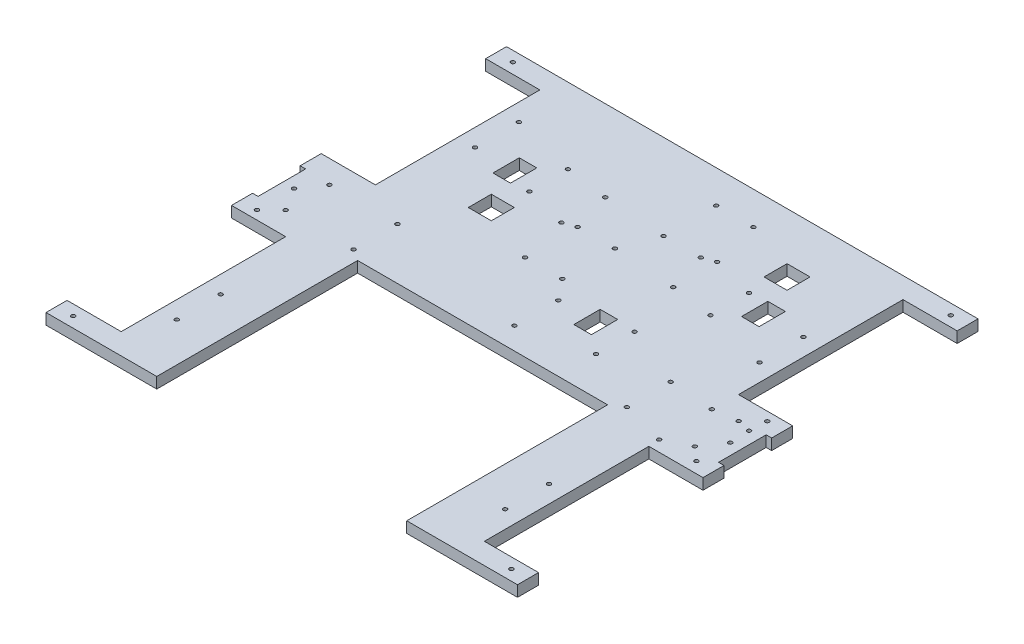
SolidWorks part; units mm, degrees
material "Acrylic (Medium-high impact)"
ref_plane "Front Plane" through (0, 0, 0) normal (0, 0, 1) x (1, 0, 0)
ref_plane "Top Plane" through (0, 0, 0) normal (0, 1, 0) x (1, 0, 0)
ref_plane "Right Plane" through (0, 0, 0) normal (1, 0, 0) x (0, 0, -1)
sketch "Sketch1" plane through (0, 0, 0) normal (0, 1, 0) x (1, 0, 0)
  line L0 (0, 0) -> (60.96, 0)
  line L2 (0, 0) -> (0, 266.7)
  line L3 (0, 266.7) -> (266.7, 266.7)
  line L4 (266.7, 0) -> (266.7, 266.7)
  line L5 (266.7, 0) -> (205.74, 0)
  line L6 (60.96, 0) -> (60.96, 116.332)
  line L7 (60.96, 116.332) -> (205.74, 116.332)
  line L8 (205.74, 116.332) -> (205.74, 0)
  line L9 (131.445, 116.332) -> (144.399, 116.332) construction
  dimension "D1" = 266.7
  dimension "D2" = 60.96
extrude "Boss-Extrude1" add sketch "Sketch1" along normal blind 6.35
sketch "Sketch3" plane through (0, 0, 0) normal (0, -1, 0) x (1, 0, 0)
  line L1 (6.5151, -160.02) -> (260.1849, -160.02) construction
  line L2 (6.5151, -160.02) -> (6.5151, -254) construction
  line L3 (6.5151, -254) -> (260.1849, -254) construction
  line L4 (260.1849, -160.02) -> (260.1849, -254) construction
  line L5 (200.2409, -199.39) -> (210.4009, -199.39)
  line L6 (56.2737, -199.39) -> (66.4337, -199.39)
  line L7 (56.2737, -199.39) -> (56.2737, -214.63)
  line L8 (56.2737, -214.63) -> (66.4337, -214.63)
  line L9 (66.4337, -199.39) -> (66.4337, -214.63)
  line L10 (200.2409, -199.39) -> (200.2409, -214.63)
  line L11 (200.2409, -214.63) -> (210.4009, -214.63)
  line L12 (210.4009, -199.39) -> (210.4009, -214.63)
  line L13 (266.7, -266.7) -> (0, -266.7) construction
  circle A0 centre (38.2651, -232.41) radius 1.1303
  circle A1 centre (38.2651, -207.01) radius 1.1303
  circle A2 centre (76.0857, -223.012) radius 1.1303
  circle A3 centre (76.0857, -200.66) radius 1.1303
  circle A4 centre (107.8611, -166.37) radius 1.1303
  circle A5 centre (107.8611, -196.85) radius 1.1303
  circle A6 centre (129.4511, -166.37) radius 1.1303
  circle A7 centre (129.4511, -196.85) radius 1.1303
  circle A8 centre (137.2743, -217.17) radius 1.1303
  circle A9 centre (158.8643, -217.17) radius 1.1303
  circle A10 centre (137.2743, -247.65) radius 1.1303
  circle A11 centre (158.8643, -247.65) radius 1.1303
  circle A12 centre (190.5889, -191.008) radius 1.1303
  circle A13 centre (190.5889, -213.36) radius 1.1303
  circle A14 centre (228.4349, -181.61) radius 1.1303
  circle A15 centre (228.4349, -207.01) radius 1.1303
  point P6 (133.35, -266.7)
  point P7 (133.35, -160.02)
  point P52 (133.35, -254)
  dimension "D4" = 10.16
  dimension "D30" = 31.75
  dimension "D12" = 2.2606
  dimension "D1" = 93.98
  dimension "D2" = 253.6698
  dimension "D3" = 12.7
  dimension "D5" = 15.24
  dimension "D6" = 25.4
  dimension "D7" = 31.75
  dimension "D8" = 30.48
  dimension "D9" = 21.59
  dimension "D10" = 130.7592
  dimension "D11" = 6.35
  dimension "D13" = 39.37
  dimension "D14" = 21.59
  dimension "D15" = 49.7586
  dimension "D16" = 22.352
  dimension "D17" = 69.5706
  dimension "D18" = 30.988
  dimension "D19" = 21.59
  dimension "D20" = 30.48
  dimension "D21" = 152.3238
  dimension "D22" = 6.35
  dimension "D23" = 22.352
  dimension "D24" = 30.988
  dimension "D25" = 69.596
  dimension "D26" = 49.784
  dimension "D27" = 39.37
  dimension "D28" = 25.4
  dimension "D29" = 21.59
extrude "Cut-Extrude1" cut sketch "Sketch3" against normal blind 6.35
sketch "Sketch5" plane through (0, 0, 0) normal (0, 1, 0) x (1, 0, 0)
  line L0 (0, 266.7) -> (0, 0) construction
  line L1 (0, 254.635) -> (28.194, 254.635)
  line L2 (0, 254.635) -> (0, 159.385)
  line L3 (0, 159.385) -> (28.194, 159.385)
  line L4 (28.194, 254.635) -> (28.194, 159.385)
  line L5 (266.7, 0) -> (266.7, 266.7) construction
  line L6 (266.7, 254.635) -> (238.506, 254.635)
  line L7 (266.7, 254.635) -> (266.7, 159.385)
  line L8 (266.7, 159.385) -> (238.506, 159.385)
  line L9 (238.506, 254.635) -> (238.506, 159.385)
  line L10 (266.7, 107.442) -> (238.506, 107.442)
  line L11 (266.7, 107.442) -> (266.7, 12.192)
  line L12 (266.7, 12.192) -> (238.506, 12.192)
  line L13 (238.506, 107.442) -> (238.506, 12.192)
  line L14 (266.7, 266.7) -> (0, 266.7) construction
  line L15 (205.74, 0) -> (266.7, 0) construction
  line L16 (266.7, 0) -> (266.7, 266.7) construction
  line L17 (28.194, 107.442) -> (0, 107.442)
  line L18 (28.194, 107.442) -> (28.194, 12.192)
  line L19 (28.194, 12.192) -> (0, 12.192)
  line L20 (0, 107.442) -> (0, 12.192)
  line L21 (0, 0) -> (60.96, 0) construction
  point P6 (28.194, 207.01)
  point P17 (238.506, 207.01)
  dimension "D1" = 95.25
  dimension "D2" = 28.194
  dimension "D3" = 95.25
  dimension "D4" = 28.194
  dimension "D5" = 12.065
  dimension "D6" = 12.192
  dimension "D7" = 12.192
extrude "Cut-Extrude2" cut sketch "Sketch5" along normal blind 6.35
sketch "Sketch6" plane through (0, 6.35, 0) normal (0, 1, 0) x (1, 0, 0)
  line L0 (129.4511, 196.85) -> (129.4511, 166.37) construction
  line L1 (66.4337, 188.2789) -> (79.7715, 188.2789)
  line L2 (66.4337, 188.2789) -> (66.4337, 174.9411)
  line L3 (66.4337, 174.9411) -> (79.7715, 174.9411)
  line L4 (79.7715, 188.2789) -> (79.7715, 174.9411)
  line L5 (137.2743, 247.65) -> (137.2743, 217.17) construction
  line L7 (186.9031, 239.0789) -> (200.2409, 239.0789)
  line L8 (186.9031, 239.0789) -> (186.9031, 225.7411)
  line L9 (186.9031, 225.7411) -> (200.2409, 225.7411)
  line L10 (200.2409, 239.0789) -> (200.2409, 225.7411)
  line L12 (66.4337, 214.63) -> (66.4337, 199.39) construction
  line L13 (200.2409, 199.39) -> (200.2409, 214.63) construction
  point P8 (129.4511, 181.61)
  point P9 (66.4337, 181.61)
  point P19 (200.2409, 232.41)
  point P20 (137.2743, 232.41)
extrude "Cut-Extrude3" cut sketch "Sketch6" against normal blind 6.35
sketch "Sketch7" plane through (0, 0, 0) normal (0, -1, 0) x (1, 0, 0)
  line L0 (0, -159.385) -> (0, -107.442) construction
  line L1 (28.194, -107.442) -> (0, -107.442) construction
  line L2 (0, -159.385) -> (28.194, -159.385) construction
  line L3 (266.7, -107.442) -> (266.7, -159.385) construction
  line L4 (266.7, -107.442) -> (238.506, -107.442) construction
  line L5 (238.506, -159.385) -> (266.7, -159.385) construction
  line L7 (0, 0) -> (60.96, 0) construction
  circle A0 centre (3.81, -113.792) radius 1.1303 construction
  circle A1 centre (3.81, -153.035) radius 1.1303 construction
  circle A2 centre (262.89, -113.792) radius 1.1303 construction
  circle A5 centre (262.89, -153.035) radius 1.1303 construction
  circle A6 centre (44.45, -113.792) radius 1.1303 construction
  circle A7 centre (44.45, -153.035) radius 1.1303 construction
  circle A8 centre (222.25, -113.792) radius 1.1303 construction
  circle A9 centre (222.25, -153.035) radius 1.1303 construction
  circle A10 centre (38.2651, -34.29) radius 1.1303
  circle A11 centre (38.2651, -59.69) radius 1.1303
  circle A12 centre (228.4349, -34.29) radius 1.1303
  circle A13 centre (228.4349, -59.69) radius 1.1303
  dimension "D1" = 2.2606
  dimension "D2" = 3.81
  dimension "D3" = 6.35
  dimension "D4" = 6.35
  dimension "D5" = 3.81
  dimension "D6" = 3.81
  dimension "D7" = 6.35
  dimension "D8" = 6.35
  dimension "D9" = 40.64
  dimension "D10" = 40.64
  dimension "D11" = 39.243
  dimension "D12" = 25.4
  dimension "D14" = 34.29
extrude "Cut-Extrude4" cut sketch "Sketch7" against normal blind 16.002
sketch "Sketch8" plane through (0, 6.35, 0) normal (0, 1, 0) x (1, 0, 0)
  line L0 (266.7, 107.442) -> (266.7, 159.385) construction
  line L2 (14.859, 146.1135) -> (14.859, 120.7135) construction
  line L3 (0, 159.385) -> (0, 107.442) construction
  line L4 (14.859, 146.1135) -> (54.229, 146.1135) construction
  line L5 (28.194, 159.385) -> (28.194, 254.635) construction
  line L6 (212.471, 146.1135) -> (251.841, 146.1135) construction
  line L7 (155.702, 162.052) -> (165.862, 162.052)
  line L8 (238.506, 254.635) -> (238.506, 159.385) construction
  line L9 (155.702, 162.052) -> (155.702, 146.812)
  line L10 (155.702, 146.812) -> (165.862, 146.812)
  line L11 (165.862, 162.052) -> (165.862, 146.812)
  line L13 (238.506, 159.385) -> (266.7, 159.385) construction
  circle A0 centre (14.859, 146.1135) radius 1.1303
  circle A1 centre (14.859, 120.7135) radius 1.1303
  circle A2 centre (107.8611, 166.37) radius 1.1303 construction
  circle A3 centre (54.229, 146.1135) radius 1.1303
  circle A4 centre (54.229, 120.7135) radius 1.1303
  circle A5 centre (212.471, 146.1135) radius 1.1303
  circle A6 centre (212.471, 120.7135) radius 1.1303
  circle A8 centre (251.841, 120.7135) radius 1.1303
  circle A9 centre (251.841, 146.1135) radius 1.1303
  circle A10 centre (139.065, 154.432) radius 1.1303
  circle A11 centre (139.065, 129.032) radius 1.1303
  circle A14 centre (176.911, 160.782) radius 1.1303
  circle A16 centre (176.911, 138.43) radius 1.1303
  circle A17 centre (238.125, 144.272) radius 1.1303
  circle A18 centre (238.125, 113.792) radius 1.1303
  circle A19 centre (259.715, 144.272) radius 1.1303
  circle A20 centre (259.715, 113.792) radius 1.1303
  point P8 (232.156, 146.1135)
  point P10 (0, 133.4135)
  point P11 (14.859, 133.4135)
  point P17 (34.544, 146.1135)
  point P23 (160.782, 162.052)
  dimension "D1" = 25.4
  dimension "D2" = 39.37
  dimension "D3" = 6.35
  dimension "D4" = 39.37
  dimension "D5" = 6.35
  dimension "D6" = 6.985
  dimension "D7" = 15.113
  dimension "D8" = 30.48
  dimension "D9" = 21.59
  dimension "D10" = 21.59
  dimension "D11" = 61.214
  dimension "D12" = 22.352
  dimension "D13" = 5.842
  dimension "D14" = 10.16
  dimension "D15" = 15.24
  dimension "D16" = 16.129
  dimension "D17" = 1.27
  dimension "D18" = 25.4
  dimension "D19" = 37.846
  dimension "D20" = 7.62
extrude "Cut-Extrude5" cut sketch "Sketch8" against normal blind 6.35
sketch "Sketch9" plane through (0, 0, 0) normal (-1, 0, 0) x (0, 0, 1)
  line L0 (-159.385, 0) -> (-107.442, 0) construction
  line L1 (-266.7, 6.35) -> (-254.635, 6.35)
  line L2 (-266.7, 6.35) -> (-266.7, 0)
  line L3 (-266.7, 0) -> (-254.635, 0)
  line L4 (-254.635, 6.35) -> (-254.635, 0)
  line L5 (-12.192, 6.35) -> (0, 6.35)
  line L6 (-12.192, 6.35) -> (-12.192, 0)
  line L7 (-12.192, 0) -> (0, 0)
  line L8 (0, 6.35) -> (0, 0)
  line L9 (-159.385, 6.35) -> (-147.193, 6.35)
  line L10 (-159.385, 6.35) -> (-159.385, 0)
  line L11 (-159.385, 0) -> (-147.193, 0)
  line L12 (-147.193, 6.35) -> (-147.193, 0)
  line L13 (-159.385, 6.35) -> (-107.442, 6.35) construction
  line L14 (-107.442, 0) -> (-119.634, 0)
  line L15 (-107.442, 0) -> (-107.442, 6.35)
  line L16 (-107.442, 6.35) -> (-119.634, 6.35)
  line L17 (-119.634, 0) -> (-119.634, 6.35)
  dimension "D1" = 12.065
  dimension "D2" = 6.35
  dimension "D3" = 12.192
  dimension "D4" = 12.192
extrude "Boss-Extrude2" add sketch "Sketch9" along normal blind 3.175
sketch "Sketch10" plane through (266.7, 0, 0) normal (1, 0, 0) x (0, 0, -1)
  line L0 (107.442, 0) -> (159.385, 0) construction
  line L1 (0, 6.35) -> (12.192, 6.35)
  line L2 (0, 6.35) -> (0, 0)
  line L3 (0, 0) -> (12.192, 0)
  line L4 (12.192, 6.35) -> (12.192, 0)
  line L5 (107.442, 6.35) -> (119.634, 6.35)
  line L6 (107.442, 6.35) -> (107.442, 0)
  line L7 (107.442, 0) -> (119.634, 0)
  line L8 (119.634, 6.35) -> (119.634, 0)
  line L9 (159.385, 6.35) -> (147.193, 6.35)
  line L10 (159.385, 6.35) -> (159.385, 0)
  line L11 (159.385, 0) -> (147.193, 0)
  line L12 (147.193, 6.35) -> (147.193, 0)
  line L13 (254.635, 6.35) -> (266.7, 6.35) construction
  line L14 (254.635, 0) -> (266.7, 0)
  line L15 (254.635, 0) -> (254.635, 6.35)
  line L16 (254.635, 6.35) -> (266.7, 6.35)
  line L17 (266.7, 0) -> (266.7, 6.35)
  dimension "D1" = 12.192
  dimension "D2" = 12.192
extrude "Boss-Extrude3" add sketch "Sketch10" along normal blind 3.175
sketch "Sketch12" plane through (0, 6.35, 0) normal (0, 1, 0) x (1, 0, 0)
  circle A0 centre (100.965, 219.71) radius 1.1303
  circle A1 centre (107.8611, 166.37) radius 1.1303 construction
  circle A2 centre (100.965, 194.31) radius 1.1303
  circle A3 centre (165.735, 219.71) radius 1.1303
  circle A6 centre (165.735, 194.31) radius 1.1303
extrude "Cut-Extrude7" cut sketch "Sketch12" against normal blind 19.05
sketch "Sketch14" plane through (0, 0, 0) normal (0, -1, 0) x (1, 0, 0)
  circle A0 centre (6.477, -133.985) radius 1.1303
  circle A1 centre (6.477, -112.522) radius 1.1303
  circle A2 centre (260.223, -132.842) radius 1.1303
  circle A3 centre (260.223, -154.305) radius 1.1303
  dimension "D1" = 2.2606
  dimension "D2" = 2.2606
  dimension "D3" = 2.2606
extrude "Cut-Extrude8" cut sketch "Sketch14" against normal blind 6.35
sketch "Sketch15" plane through (0, 0, 0) normal (0, -1, 0) x (1, 0, 0)
  circle A0 centre (6.477, -6.096) radius 1.1303
  circle A1 centre (6.477, -260.7224) radius 1.1303
  circle A2 centre (260.223, -260.604) radius 1.1303
  circle A3 centre (260.223, -6.096) radius 1.1303
  dimension "D1" = 2.2606
  dimension "D2" = 2.2606
  dimension "D3" = 2.2606
  dimension "D4" = 2.2606
extrude "Cut-Extrude9" cut sketch "Sketch15" against normal blind 6.35
